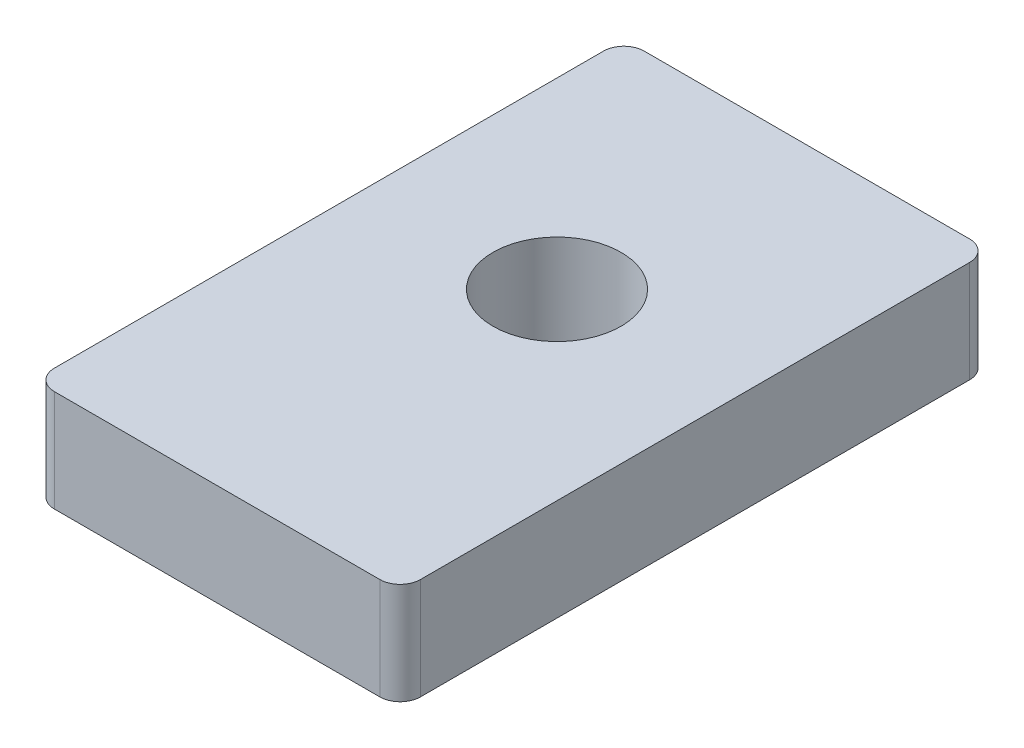
SolidWorks part; units mm, degrees
ref_plane "前视基准面" through (0, 0, 0) normal (0, 0, 1) x (1, 0, 0)
ref_plane "上视基准面" through (0, 0, 0) normal (0, 1, 0) x (1, 0, 0)
ref_plane "右视基准面" through (0, 0, 0) normal (1, 0, 0) x (0, 0, -1)
other "Configuration Table"
sketch "草图1" plane through (0, 0, 0) normal (0, 0, 1) x (1, 0, 0)
  line L0 (0, 0) -> (36, 0)
  line L1 (36, 0) -> (36, 10)
  line L2 (36, 10) -> (0, 10)
  line L3 (0, 10) -> (0, 0)
  dimension "width" = 36
  dimension "height" = 10
extrude "BlockExtrude" add sketch "草图1" along normal blind 58
fillet "Fillet" radius 2 4 edges at (0, 5, 0) (36, 5, 0) (0, 5, 58) (36, 5, 58)
sketch "草图2" plane through (0, 10, 0) normal (0, 1, 0) x (1, 0, 0)
  circle A0 centre (18, -24.5744) radius 6.3
  dimension "diameter" = 12.6
  dimension "x" = 18
  dimension "y" = 24.5744
extrude "Drive_shaft_passage" cut sketch "草图2" against normal through all
